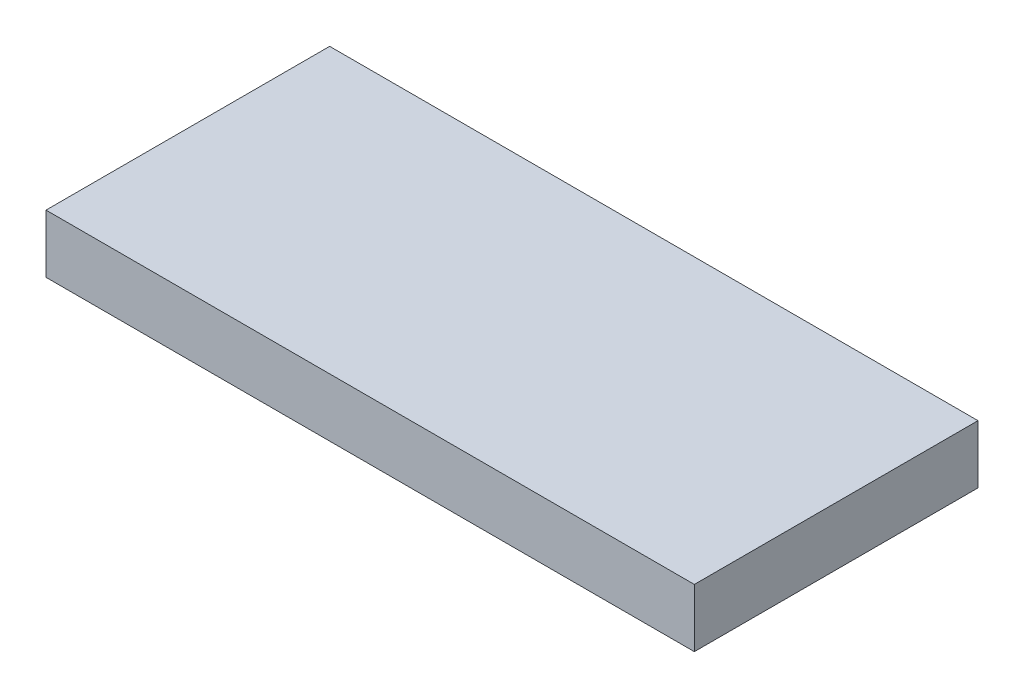
SolidWorks part; units mm, degrees
material "Pine"
ref_plane "Front Plane" through (0, 0, 0) normal (0, 0, 1) x (1, 0, 0)
ref_plane "Top Plane" through (0, 0, 0) normal (0, 1, 0) x (1, 0, 0)
ref_plane "Right Plane" through (0, 0, 0) normal (1, 0, 0) x (0, 0, -1)
sketch "Sketch1" plane through (0, 0, 0) normal (0, 1, 0) x (1, 0, 0)
  line L1 (-101.6, 44.45) -> (101.6, 44.45)
  line L2 (-101.6, 44.45) -> (-101.6, -44.45)
  line L3 (-101.6, -44.45) -> (101.6, -44.45)
  line L4 (101.6, 44.45) -> (101.6, -44.45)
  line L5 (0, -44.45) -> (0, 44.45) construction
  line L6 (-101.6, 0) -> (101.6, 0) construction
  point P0 (0, 0)
  dimension "D1" = 88.9
  dimension "D2" = 203.2
extrude "Boss-Extrude1" add sketch "Sketch1" along normal blind 18.2562
